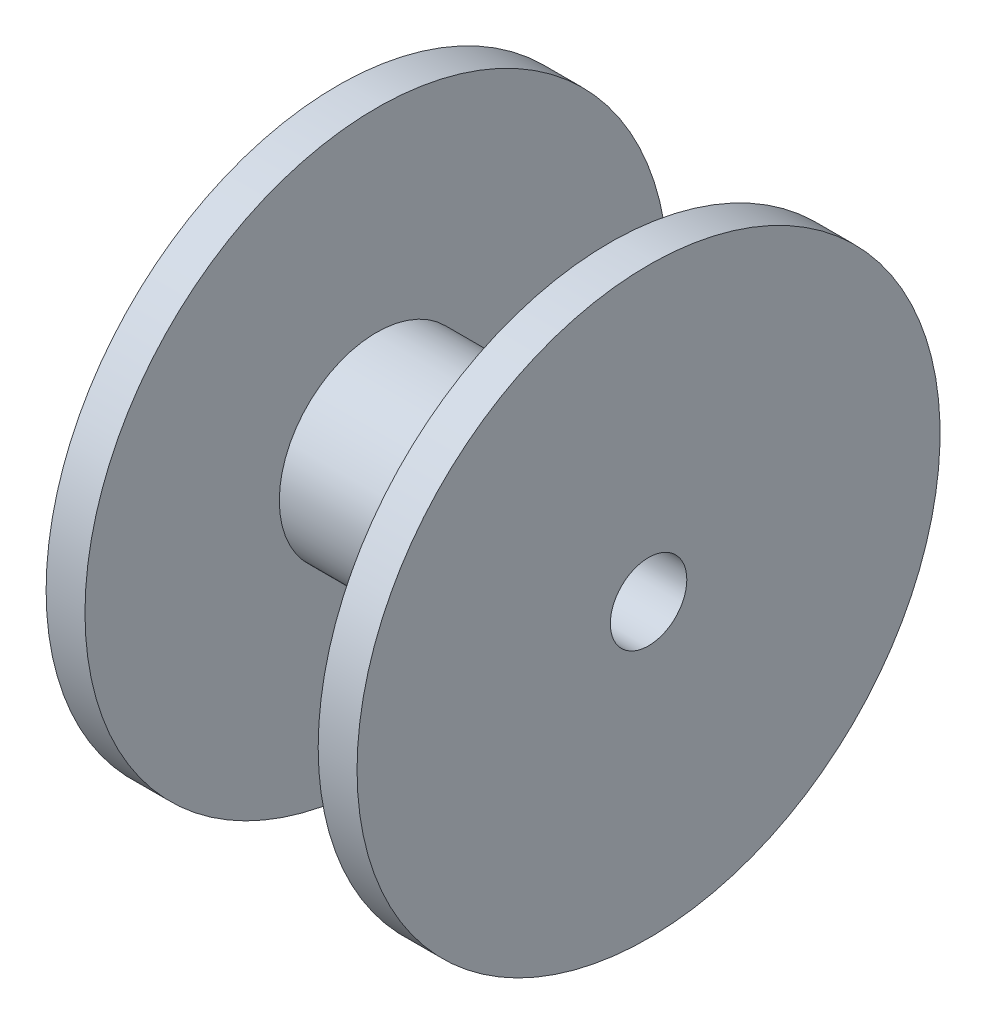
SolidWorks part; units mm, degrees
ref_plane "Front Plane" through (0, 0, 0) normal (0, 0, 1) x (1, 0, 0)
ref_plane "Top Plane" through (0, 0, 0) normal (0, 1, 0) x (1, 0, 0)
ref_plane "Right Plane" through (0, 0, 0) normal (1, 0, 0) x (0, 0, -1)
sketch "Sketch1" plane through (0, 0, 0) normal (0, 0, 1) x (1, 0, 0)
  line L0 (0, 0) -> (40.64, 0)
  line L1 (0, 0) -> (0, -38.1)
  line L2 (5.08, -38.1) -> (0, -38.1)
  line L3 (5.08, -38.1) -> (5.08, -12.7)
  line L4 (5.08, -12.7) -> (35.56, -12.7)
  line L5 (35.56, -12.7) -> (35.56, -38.1)
  line L6 (35.56, -38.1) -> (40.64, -38.1)
  line L7 (40.64, -38.1) -> (40.64, 0)
  dimension "D1" = 40.64
  dimension "D2" = 38.1
  dimension "D3" = 25.4
  dimension "0.2in" = 5.08
  dimension "D4" = 30.48
revolve "Revolve1" add sketch "Sketch1" angle 360 about L0
sketch "Sketch2" plane through (40.64, 0, 0) normal (1, 0, 0) x (0, 0, -1)
  circle A0 centre (0, 0) radius 5
extrude "Cut-Extrude1" cut sketch "Sketch2" against normal blind 40.64
